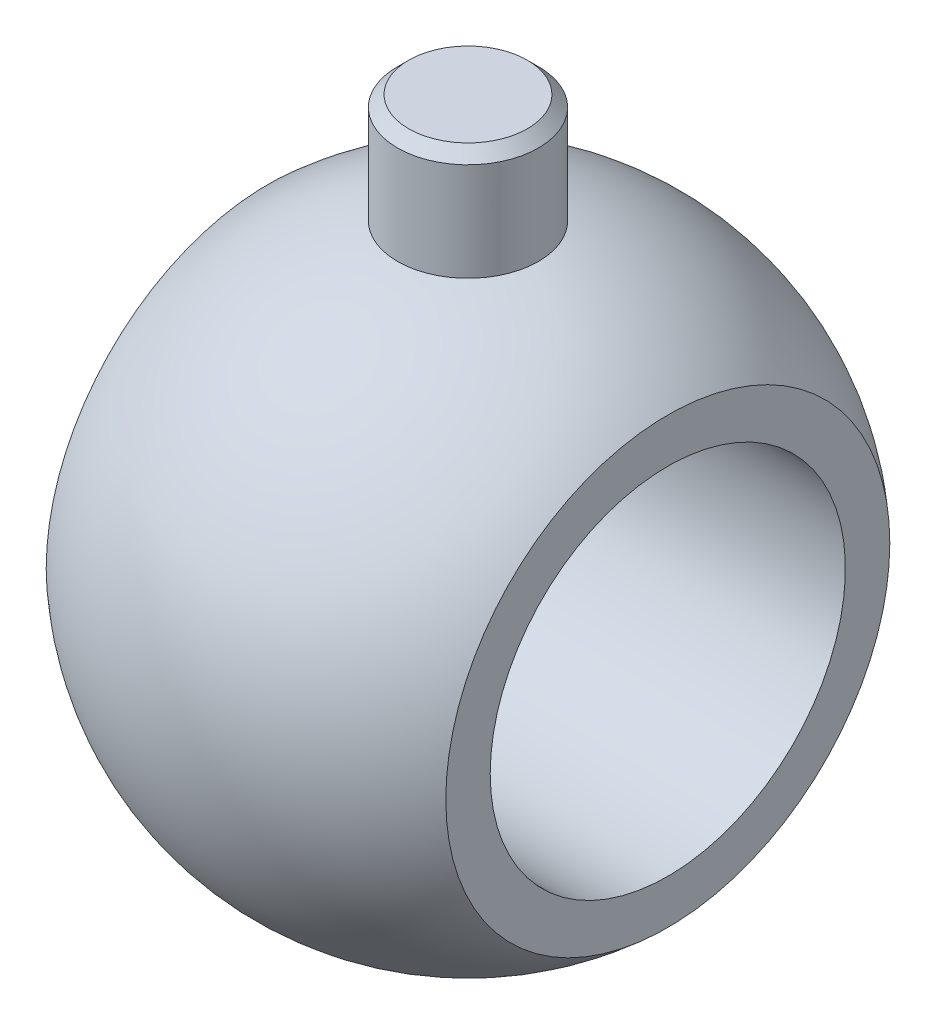
SolidWorks part; units mm, degrees
material "Bronze Alumínio"
ref_plane "Plano frontal" through (0, 0, 0) normal (0, 0, 1) x (1, 0, 0)
ref_plane "Plano superior" through (0, 0, 0) normal (0, 1, 0) x (1, 0, 0)
ref_plane "Plano direito" through (0, 0, 0) normal (1, 0, 0) x (0, 0, -1)
sketch "Esboço1" plane through (0, 0, 0) normal (0, 0, 1) x (1, 0, 0)
  line L0 (-9, 10) -> (-9, 8)
  line L2 (9, 8) -> (9, 10)
  line L3 (0, 0) -> (14.8759, 0) construction
  line L4 (-9, 8) -> (9, 8)
  arc A0 (9, 10) -> (-9, 10) centre (0, 0) ccw
  point P1 (0, 0)
  point P5 (0, 0)
  point P11 (0.357, 4.1655)
  dimension "D1" = 10
  dimension "D2" = 9
  dimension "D3" = 9
  dimension "D4" = 8
revolve "Revolução1" add sketch "Esboço1" angle 360 about L3
ref_plane "Plano1" through (0, 18, 0) normal (0, 1, 0) x (1, 0, 0)
sketch "Esboço2" plane through (0, 18, 0) normal (0, 1, 0) x (1, 0, 0)
  circle A0 centre (0, 0) radius 3.175
  dimension "D3" = 6.35
  dimension "D1" = 0
  dimension "D2" = 0
extrude "Ressalto-extrusão1" add sketch "Esboço2" against normal up to surface (4.9264 mm away)
chamfer "Chanfro1" distance 0.5 angle 45 1 edges at (0, 18, 3.175)
